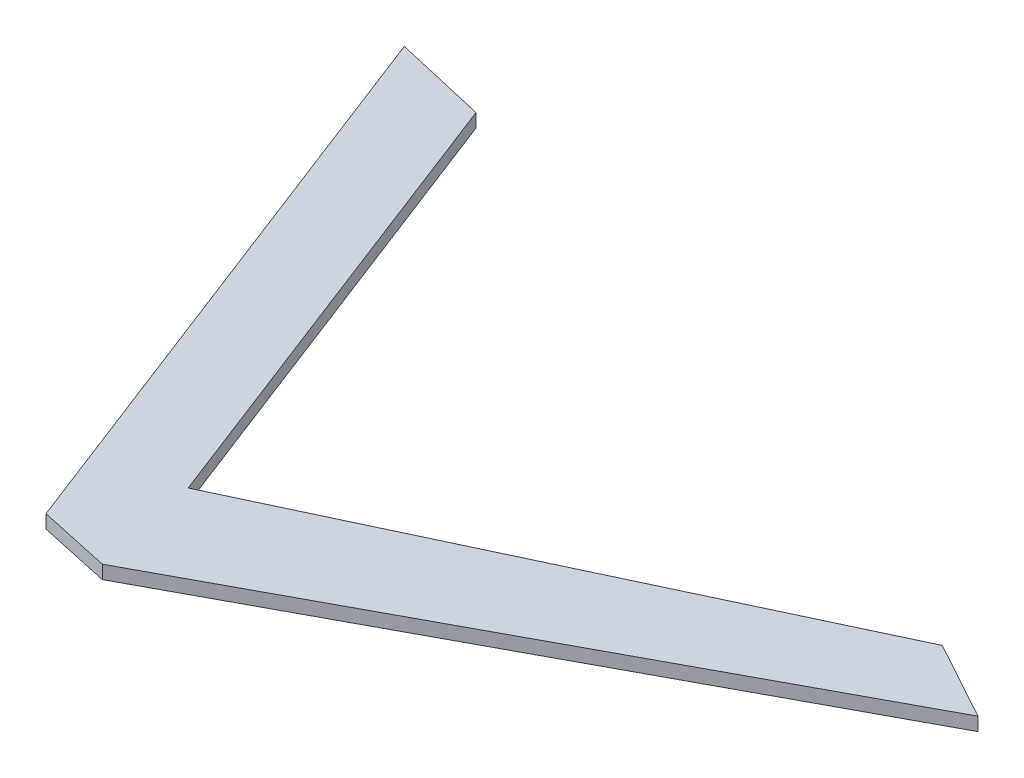
SolidWorks part; units mm, degrees
ref_plane "Front Plane" through (0, 0, 0) normal (0, 0, 1) x (1, 0, 0)
ref_plane "Top Plane" through (0, 0, 0) normal (0, 1, 0) x (1, 0, 0)
ref_plane "Right Plane" through (0, 0, 0) normal (1, 0, 0) x (0, 0, -1)
sketch "Sketch1" plane through (0, 0, 0) normal (0, 1, 0) x (1, 0, 0)
  line L0 (0, 0) -> (-13.5483, 35.0742)
  line L1 (-13.5483, 35.0742) -> (-20.5162, 36.678)
  line L2 (-20.5162, 36.678) -> (-3.6528, -6.9783)
  line L3 (-3.6528, -6.9783) -> (1.7223, -8.1437)
  line L4 (1.7223, -8.1437) -> (44.3074, 14.7525)
  line L5 (44.3074, 14.7525) -> (38.3897, 17.9997)
  line L6 (38.3897, 17.9997) -> (0, 0)
  point P8 (-9.7567, -11.145)
  point P9 (-9.7567, -11.145)
  point P10 (46.8487, 7.5293)
  point P11 (1.4951, -7.1061)
  point P12 (44.3074, 14.7525)
  dimension "D1" = 86
  dimension "D2" = 37.6
  dimension "D3" = 7.15
  dimension "D4" = 46.8
  dimension "D5" = 5.5
  dimension "D6" = 48.35
  dimension "D7" = 6.75
  dimension "D8" = 42.4
extrude "Boss-Extrude1" add sketch "Sketch1" along normal blind 1
